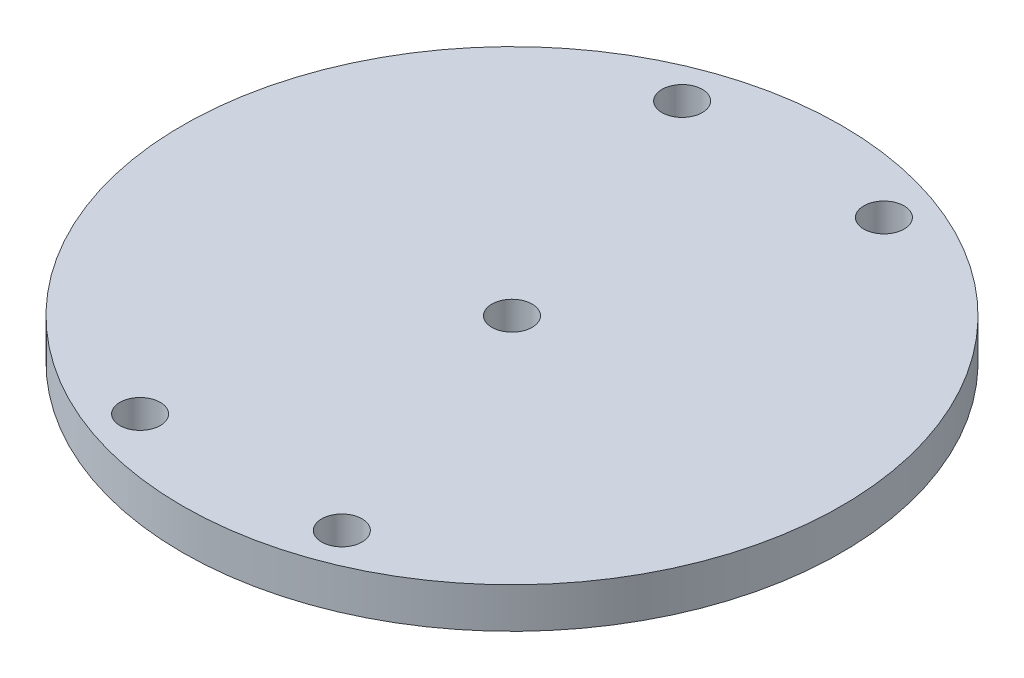
SolidWorks part; units mm, degrees
ref_plane "Front Plane" through (0, 0, 0) normal (0, 0, 1) x (1, 0, 0)
ref_plane "Top Plane" through (0, 0, 0) normal (0, 1, 0) x (1, 0, 0)
ref_plane "Right Plane" through (0, 0, 0) normal (1, 0, 0) x (0, 0, -1)
sketch "Sketch1" plane through (0, 0, 0) normal (0, 1, 0) x (1, 0, 0)
  circle A0 centre (0, 0) radius 49
  dimension "D1" = 98
extrude "Boss-Extrude1" add sketch "Sketch1" along normal blind 6
sketch "Sketch2" plane through (0, 6, 0) normal (0, 1, 0) x (1, 0, 0)
  circle A0 centre (0, 0) radius 3
  circle A1 centre (-15, 40.2989) radius 3
  circle A2 centre (15, 40.2989) radius 3
  circle A3 centre (-15, -40.2989) radius 3
  circle A4 centre (15, -40.2989) radius 3
  arc A5 (-17.7733, 39.1549) -> (-17.7733, -39.1549) centre (0, 0) ccw
  arc A6 (12.1537, 41.2467) -> (-12.1537, 41.2467) centre (0, 0) ccw
  arc A7 (17.7733, -39.1549) -> (17.7733, 39.1549) centre (0, 0) ccw
  arc A8 (-12.1537, -41.2467) -> (12.1537, -41.2467) centre (0, 0) ccw
  dimension "D1" = 6
  dimension "D2" = 6
  dimension "D3" = 6
  dimension "D4" = 6
  dimension "D5" = 6
  dimension "D6" = 86
  dimension "D7" = 30
  dimension "D8" = 30
  dimension "D9" = 15
  dimension "D10" = 15
extrude "Cut-Extrude1" cut sketch "Sketch2" against normal blind 6 contours A1 | A2 | A0 | A4 | A3
cosmetic thread "Cosmetic Thread1" parameters "D2"=7.2
cosmetic thread "Cosmetic Thread2" parameters "D2"=7.2
cosmetic thread "Cosmetic Thread3" parameters "D2"=7.2
cosmetic thread "Cosmetic Thread4" parameters "D2"=7.2
cosmetic thread "Cosmetic Thread5" parameters "D2"=7.2
